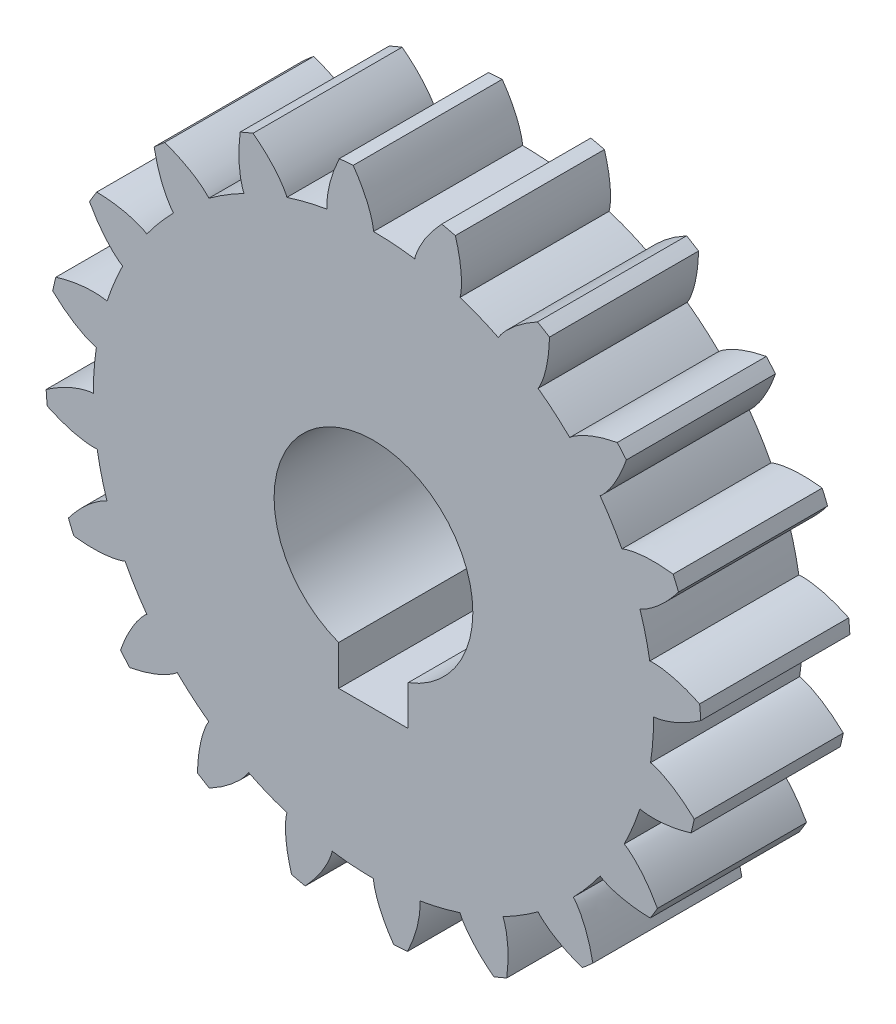
SolidWorks part; units mm, degrees
ref_plane "Front Plane" through (0, 0, 0) normal (0, 0, 1) x (1, 0, 0)
ref_plane "Top Plane" through (0, 0, 0) normal (0, 1, 0) x (1, 0, 0)
ref_plane "Right Plane" through (0, 0, 0) normal (1, 0, 0) x (0, 0, -1)
sketch "Sketch2" plane through (0, 0, 0) normal (0, 0, 1) x (1, 0, 0)
  line L1 (-3.5, -13.3675) -> (3.5, -13.3675)
  line L2 (-3.5, -13.3675) -> (-3.5, -9.3675)
  line L4 (3.5, -13.3675) -> (3.5, -9.3675)
  arc A2 (-4.1537, -27.8823) -> (0, -28.19) centre (0, 0) ccw
  arc A3 (-30.6942, -12.1188) -> (-30.1513, -13.4126) centre (0, 0) ccw
  arc A4 (-32.9368, -2.0406) -> (-32.8203, -3.4389) centre (0, 0) ccw
  arc A5 (-31.9554, 8.2373) -> (-32.2767, 6.8715) centre (0, 0) ccw
  arc A6 (-27.8459, 17.7089) -> (-28.5735, 16.5092) centre (0, 0) ccw
  arc A7 (-21.0107, 25.447) -> (-22.0734, 24.5309) centre (0, 0) ccw
  arc A8 (-12.1188, 30.6942) -> (-13.4126, 30.1513) centre (0, 0) ccw
  arc A9 (-2.0406, 32.9368) -> (-3.4389, 32.8203) centre (0, 0) ccw
  arc A10 (8.2373, 31.9554) -> (6.8715, 32.2767) centre (0, 0) ccw
  arc A11 (17.7089, 27.8459) -> (16.5092, 28.5735) centre (0, 0) ccw
  arc A12 (25.447, 21.0107) -> (24.5309, 22.0734) centre (0, 0) ccw
  arc A13 (30.6942, 12.1188) -> (30.1513, 13.4126) centre (0, 0) ccw
  arc A14 (-25.447, -21.0107) -> (-24.5309, -22.0734) centre (0, 0) ccw
  arc A15 (-17.7089, -27.8459) -> (-16.5092, -28.5735) centre (0, 0) ccw
  arc A16 (-8.2373, -31.9554) -> (-6.8715, -32.2767) centre (0, 0) ccw
  arc A17 (2.0406, -32.9368) -> (3.4389, -32.8203) centre (0, 0) ccw
  arc A18 (12.1188, -30.6942) -> (13.4126, -30.1513) centre (0, 0) ccw
  arc A19 (21.0107, -25.447) -> (22.0734, -24.5309) centre (0, 0) ccw
  arc A20 (27.8459, -17.7089) -> (28.5735, -16.5092) centre (0, 0) ccw
  arc A21 (31.9554, -8.2373) -> (32.2767, -6.8715) centre (0, 0) ccw
  arc A22 (32.9368, 2.0406) -> (32.8203, 3.4389) centre (0, 0) ccw
  arc A23 (4.6657, -27.8012) -> (8.7112, -26.8103) centre (0, 0) ccw
  arc A24 (13.0284, -24.9987) -> (16.5697, -22.8062) centre (0, 0) ccw
  arc A25 (20.1158, -19.7492) -> (22.8062, -16.5697) centre (0, 0) ccw
  arc A26 (25.2341, -12.5665) -> (26.8103, -8.7112) centre (0, 0) ccw
  arc A27 (27.8823, -4.1537) -> (28.19, 0) centre (0, 0) ccw
  arc A28 (27.8012, 4.6657) -> (26.8103, 8.7112) centre (0, 0) ccw
  arc A29 (24.9987, 13.0284) -> (22.8062, 16.5697) centre (0, 0) ccw
  arc A30 (19.7492, 20.1158) -> (16.5697, 22.8062) centre (0, 0) ccw
  arc A31 (12.5665, 25.2341) -> (8.7112, 26.8103) centre (0, 0) ccw
  arc A32 (4.1537, 27.8823) -> (0, 28.19) centre (0, 0) ccw
  arc A33 (-4.6657, 27.8012) -> (-8.7112, 26.8103) centre (0, 0) ccw
  arc A34 (-13.0284, 24.9987) -> (-16.5697, 22.8062) centre (0, 0) ccw
  arc A35 (-20.1158, 19.7492) -> (-22.8062, 16.5697) centre (0, 0) ccw
  arc A36 (-25.2341, 12.5665) -> (-26.8103, 8.7112) centre (0, 0) ccw
  arc A37 (-27.8823, 4.1537) -> (-28.19, 0) centre (0, 0) ccw
  arc A38 (-27.8012, -4.6657) -> (-26.8103, -8.7112) centre (0, 0) ccw
  arc A39 (-24.9987, -13.0284) -> (-22.8062, -16.5697) centre (0, 0) ccw
  arc A40 (-19.7492, -20.1158) -> (-16.5697, -22.8062) centre (0, 0) ccw
  arc A41 (-12.5665, -25.2341) -> (-8.7112, -26.8103) centre (0, 0) ccw
  arc A42 (3.5, -9.3675) -> (-3.5, -9.3675) centre (0, 0) ccw
  spline S0 degree 4 poles (28.19, 0) (28.213, 0.0005) (28.2774, 0.0035) (28.3988, 0.0154) (28.596, 0.0437) (28.9599, 0.1151) (29.504, 0.2622) (30.091, 0.4721) (30.6986, 0.7363) (31.2227, 0.996) (31.6344, 1.2182) (32.1251, 1.5038) (32.7029, 1.8713) (33.3591, 2.3322) (34.0832, 2.8977) (34.7923, 3.5087) (35.4729, 4.1508) (36.1257, 4.8218) (36.7504, 5.5179) (37.2738, 6.1488) (37.7044, 6.7012) (38.0537, 7.1729) (38.3236, 7.5499) (38.5928, 7.942) (38.8447, 8.3199) (39.1085, 8.7342) (39.3339, 9.0971) (39.6556, 9.6405) (39.842, 9.9691) (40.1352, 10.5002) (40.2576, 10.7404) (40.3721, 10.9571) (40.4036, 11.0214) (40.4277, 11.0683) (40.4408, 11.0936) knots 0 0 0 0 0 0.005377 0.015084 0.028532 0.04661 0.092111 0.146842 0.174209 0.201575 0.228941 0.256307 0.307035 0.361767 0.4165 0.471232 0.525964 0.580697 0.635429 0.690161 0.717528 0.744894 0.77226 0.799626 0.826992 0.854358 0.881725 0.909091 0.954545 0.977273 0.988636 0.994318 1 1 1 1 1 construction
  spline S1 degree 4 poles (28.19, 0) (28.213, 0.0005) (28.2774, 0.0035) (28.3988, 0.0154) (28.596, 0.0437) (28.9599, 0.1151) (29.504, 0.2622) (30.091, 0.4721) (30.6986, 0.7363) (31.2227, 0.996) (31.6344, 1.2182) (32.119, 1.5003) (32.4936, 1.7382) (32.7647, 1.9207) (32.9368, 2.0406) knots 0 0 0 0 0 0.005377 0.015084 0.028532 0.04661 0.092111 0.146842 0.174209 0.201575 0.228941 0.256307 0.305396 0.305396 0.305396 0.305396 0.305396
  spline S2 degree 4 poles (24.9987, 13.0284) (25.0194, 13.0385) (25.0779, 13.0656) (25.191, 13.1112) (25.379, 13.1772) (25.7347, 13.2821) (26.2852, 13.4032) (26.9027, 13.4883) (27.5637, 13.5348) (28.1484, 13.5467) (28.6162, 13.54) (29.1763, 13.5138) (29.6185, 13.4759) (29.9433, 13.4394) (30.1513, 13.4126) knots 0 0 0 0 0 0.005377 0.015084 0.028532 0.04661 0.092111 0.146842 0.174209 0.201575 0.228941 0.256307 0.305396 0.305396 0.305396 0.305396 0.305396
  spline S3 degree 4 poles (26.8103, -8.7112) (26.8323, -8.7178) (26.8945, -8.7348) (27.0136, -8.761) (27.2099, -8.7951) (27.5781, -8.8396) (28.141, -8.8679) (28.7641, -8.8496) (29.4237, -8.7862) (30.0023, -8.7011) (30.4626, -8.617) (31.0174, -8.497) (31.6805, -8.326) (32.4471, -8.0905) (33.3105, -7.7764) (34.1737, -7.4144) (35.0194, -7.014) (35.8476, -6.5777) (36.6569, -6.1087) (37.3495, -5.6704) (37.9298, -5.2781) (38.4078, -4.9375) (38.7809, -4.6623) (39.1581, -4.3725) (39.5145, -4.091) (39.8934, -3.7785) (40.2199, -3.503) (40.6938, -3.0856) (40.9726, -2.8306) (41.4156, -2.4162) (41.6062, -2.2255) (41.7821, -2.0548) (41.8319, -2.0034) (41.8693, -1.9662) (41.8896, -1.9462) knots 0 0 0 0 0 0.005377 0.015084 0.028532 0.04661 0.092111 0.146842 0.174209 0.201575 0.228941 0.256307 0.307035 0.361767 0.4165 0.471232 0.525964 0.580697 0.635429 0.690161 0.717528 0.744894 0.77226 0.799626 0.826992 0.854358 0.881725 0.909091 0.954545 0.977273 0.988636 0.994318 1 1 1 1 1 construction
  spline S4 degree 4 poles (26.8103, -8.7112) (26.8323, -8.7178) (26.8945, -8.7348) (27.0136, -8.761) (27.2099, -8.7951) (27.5781, -8.8396) (28.141, -8.8679) (28.7641, -8.8496) (29.4237, -8.7862) (30.0023, -8.7011) (30.4626, -8.617) (31.0106, -8.4984) (31.4404, -8.3879) (31.7546, -8.2982) (31.9554, -8.2373) knots 0 0 0 0 0 0.005377 0.015084 0.028532 0.04661 0.092111 0.146842 0.174209 0.201575 0.228941 0.256307 0.305396 0.305396 0.305396 0.305396 0.305396
  spline S5 degree 4 poles (27.8012, 4.6657) (27.824, 4.669) (27.888, 4.6767) (28.0097, 4.685) (28.2089, 4.6897) (28.5796, 4.6796) (29.1405, 4.6246) (29.7541, 4.5147) (30.3971, 4.3548) (30.9569, 4.1854) (31.3997, 4.0344) (31.9243, 3.8364) (32.3332, 3.6637) (32.6307, 3.5287) (32.8203, 3.4389) knots 0 0 0 0 0 0.005377 0.015084 0.028532 0.04661 0.092111 0.146842 0.174209 0.201575 0.228941 0.256307 0.305396 0.305396 0.305396 0.305396 0.305396
  spline S6 degree 4 poles (22.8062, -16.5697) (22.8251, -16.5828) (22.8789, -16.6182) (22.9842, -16.6799) (23.1604, -16.7729) (23.4967, -16.9291) (24.0234, -17.1299) (24.6216, -17.3051) (25.2685, -17.4485) (25.8451, -17.5464) (26.3088, -17.6087) (26.8736, -17.666) (27.5571, -17.7083) (28.3589, -17.7212) (29.2771, -17.6894) (30.2099, -17.6118) (31.138, -17.4924) (32.0605, -17.3333) (32.9751, -17.1373) (33.7693, -16.9345) (34.4423, -16.7407) (35.0022, -16.5645) (35.4421, -16.418) (35.8904, -16.259) (36.3163, -16.1014) (36.7732, -15.9213) (37.1689, -15.7602) (37.7486, -15.5096) (38.0925, -15.3533) (38.6419, -15.096) (38.8821, -14.9736) (39.1021, -14.8656) (39.1654, -14.8321) (39.2124, -14.8083) (39.2379, -14.7955) knots 0 0 0 0 0 0.005377 0.015084 0.028532 0.04661 0.092111 0.146842 0.174209 0.201575 0.228941 0.256307 0.307035 0.361767 0.4165 0.471232 0.525964 0.580697 0.635429 0.690161 0.717528 0.744894 0.77226 0.799626 0.826992 0.854358 0.881725 0.909091 0.954545 0.977273 0.988636 0.994318 1 1 1 1 1 construction
  spline S7 degree 4 poles (22.8062, -16.5697) (22.8251, -16.5828) (22.8789, -16.6182) (22.9842, -16.6799) (23.1604, -16.7729) (23.4967, -16.9291) (24.0234, -17.1299) (24.6216, -17.3051) (25.2685, -17.4485) (25.8451, -17.5464) (26.3088, -17.6087) (26.8667, -17.6653) (27.3096, -17.693) (27.6362, -17.7048) (27.8459, -17.7089) knots 0 0 0 0 0 0.005377 0.015084 0.028532 0.04661 0.092111 0.146842 0.174209 0.201575 0.228941 0.256307 0.305396 0.305396 0.305396 0.305396 0.305396
  spline S8 degree 4 poles (27.8823, -4.1537) (27.905, -4.1576) (27.9682, -4.1701) (28.0865, -4.1998) (28.2774, -4.2568) (28.6269, -4.381) (29.1434, -4.6066) (29.6929, -4.9008) (30.2551, -5.2516) (30.7351, -5.5857) (31.1096, -5.8661) (31.5473, -6.2166) (31.8828, -6.5071) (32.1241, -6.7275) (32.2767, -6.8715) knots 0 0 0 0 0 0.005377 0.015084 0.028532 0.04661 0.092111 0.146842 0.174209 0.201575 0.228941 0.256307 0.305396 0.305396 0.305396 0.305396 0.305396
  spline S9 degree 4 poles (16.5697, -22.8062) (16.5836, -22.8245) (16.6239, -22.8748) (16.7049, -22.966) (16.8437, -23.1089) (17.1153, -23.3614) (17.5541, -23.7152) (18.069, -24.0666) (18.6399, -24.4029) (19.158, -24.6742) (19.5798, -24.8768) (20.0993, -25.1058) (20.7362, -25.3572) (21.4948, -25.6172) (22.3779, -25.8707) (23.289, -26.0852) (24.2086, -26.2584) (25.1351, -26.3921) (26.0654, -26.4884) (26.8834, -26.541) (27.5834, -26.5646) (28.1704, -26.57) (28.634, -26.5667) (29.1095, -26.554) (29.5633, -26.5357) (30.0535, -26.5056) (30.4796, -26.4747) (31.1083, -26.4155) (31.4837, -26.3731) (32.0857, -26.2982) (32.352, -26.256) (32.5946, -26.2213) (32.6651, -26.2089) (32.7172, -26.2009) (32.7454, -26.1966) knots 0 0 0 0 0 0.005377 0.015084 0.028532 0.04661 0.092111 0.146842 0.174209 0.201575 0.228941 0.256307 0.307035 0.361767 0.4165 0.471232 0.525964 0.580697 0.635429 0.690161 0.717528 0.744894 0.77226 0.799626 0.826992 0.854358 0.881725 0.909091 0.954545 0.977273 0.988636 0.994318 1 1 1 1 1 construction
  spline S10 degree 4 poles (16.5697, -22.8062) (16.5836, -22.8245) (16.6239, -22.8748) (16.7049, -22.966) (16.8437, -23.1089) (17.1153, -23.3614) (17.5541, -23.7152) (18.069, -24.0666) (18.6399, -24.4029) (19.158, -24.6742) (19.5798, -24.8768) (20.0928, -25.103) (20.5055, -25.2662) (20.8125, -25.3783) (21.0107, -25.447) knots 0 0 0 0 0 0.005377 0.015084 0.028532 0.04661 0.092111 0.146842 0.174209 0.201575 0.228941 0.256307 0.305396 0.305396 0.305396 0.305396 0.305396
  spline S11 degree 4 poles (25.2341, -12.5665) (25.2544, -12.5772) (25.3107, -12.6086) (25.4141, -12.6734) (25.578, -12.7867) (25.872, -13.0128) (26.2935, -13.387) (26.7252, -13.8365) (27.1514, -14.3439) (27.5047, -14.81) (27.7743, -15.1924) (28.0823, -15.661) (28.3116, -16.041) (28.4729, -16.3251) (28.5735, -16.5092) knots 0 0 0 0 0 0.005377 0.015084 0.028532 0.04661 0.092111 0.146842 0.174209 0.201575 0.228941 0.256307 0.305396 0.305396 0.305396 0.305396 0.305396
  spline S12 degree 4 poles (8.7112, -26.8103) (8.7188, -26.832) (8.7415, -26.8923) (8.7904, -27.0041) (8.8783, -27.1829) (9.0586, -27.5069) (9.3666, -27.979) (9.7476, -28.4723) (10.1866, -28.9686) (10.5956, -29.3867) (10.9341, -29.7097) (11.3574, -30.088) (11.8854, -30.524) (12.5266, -31.0057) (13.2882, -31.5197) (14.0884, -32.0052) (14.9094, -32.4541) (15.7493, -32.8676) (16.6043, -33.2466) (17.366, -33.5494) (18.0245, -33.7882) (18.581, -33.9747) (19.023, -34.1148) (19.4791, -34.2497) (19.9164, -34.3725) (20.3919, -34.4953) (20.8067, -34.5976) (21.4229, -34.7356) (21.793, -34.8113) (22.3887, -34.9261) (22.655, -34.9683) (22.8965, -35.0102) (22.9674, -35.0203) (23.0194, -35.0287) (23.0476, -35.0333) knots 0 0 0 0 0 0.005377 0.015084 0.028532 0.04661 0.092111 0.146842 0.174209 0.201575 0.228941 0.256307 0.307035 0.361767 0.4165 0.471232 0.525964 0.580697 0.635429 0.690161 0.717528 0.744894 0.77226 0.799626 0.826992 0.854358 0.881725 0.909091 0.954545 0.977273 0.988636 0.994318 1 1 1 1 1 construction
  spline S13 degree 4 poles (8.7112, -26.8103) (8.7188, -26.832) (8.7415, -26.8923) (8.7904, -27.0041) (8.8783, -27.1829) (9.0586, -27.5069) (9.3666, -27.979) (9.7476, -28.4723) (10.1866, -28.9686) (10.5956, -29.3867) (10.9341, -29.7097) (11.3522, -30.0834) (11.6942, -30.3661) (11.9515, -30.5676) (12.1188, -30.6942) knots 0 0 0 0 0 0.005377 0.015084 0.028532 0.04661 0.092111 0.146842 0.174209 0.201575 0.228941 0.256307 0.305396 0.305396 0.305396 0.305396 0.305396
  spline S14 degree 4 poles (20.1158, -19.7492) (20.1318, -19.7657) (20.1756, -19.813) (20.2539, -19.9065) (20.3748, -20.0649) (20.5845, -20.3708) (20.8698, -20.8569) (21.1415, -21.4179) (21.39, -22.0321) (21.582, -22.5846) (21.7202, -23.0316) (21.8683, -23.5724) (21.969, -24.0046) (22.0346, -24.3247) (22.0734, -24.5309) knots 0 0 0 0 0 0.005377 0.015084 0.028532 0.04661 0.092111 0.146842 0.174209 0.201575 0.228941 0.256307 0.305396 0.305396 0.305396 0.305396 0.305396
  spline S15 degree 4 poles (0, -28.19) (0.0005, -28.213) (0.0035, -28.2774) (0.0154, -28.3988) (0.0437, -28.596) (0.1151, -28.9599) (0.2622, -29.504) (0.4721, -30.091) (0.7363, -30.6986) (0.996, -31.2227) (1.2182, -31.6344) (1.5038, -32.1251) (1.8713, -32.7029) (2.3322, -33.3591) (2.8977, -34.0832) (3.5087, -34.7923) (4.1508, -35.4729) (4.8218, -36.1257) (5.5179, -36.7504) (6.1488, -37.2738) (6.7012, -37.7044) (7.1729, -38.0537) (7.5499, -38.3236) (7.942, -38.5928) (8.3199, -38.8447) (8.7342, -39.1085) (9.0971, -39.3339) (9.6405, -39.6556) (9.9691, -39.842) (10.5002, -40.1352) (10.7404, -40.2576) (10.9571, -40.3721) (11.0214, -40.4036) (11.0683, -40.4277) (11.0936, -40.4408) knots 0 0 0 0 0 0.005377 0.015084 0.028532 0.04661 0.092111 0.146842 0.174209 0.201575 0.228941 0.256307 0.307035 0.361767 0.4165 0.471232 0.525964 0.580697 0.635429 0.690161 0.717528 0.744894 0.77226 0.799626 0.826992 0.854358 0.881725 0.909091 0.954545 0.977273 0.988636 0.994318 1 1 1 1 1 construction
  spline S16 degree 4 poles (0, -28.19) (0.0005, -28.213) (0.0035, -28.2774) (0.0154, -28.3988) (0.0437, -28.596) (0.1151, -28.9599) (0.2622, -29.504) (0.4721, -30.091) (0.7363, -30.6986) (0.996, -31.2227) (1.2182, -31.6344) (1.5003, -32.119) (1.7382, -32.4936) (1.9207, -32.7647) (2.0406, -32.9368) knots 0 0 0 0 0 0.005377 0.015084 0.028532 0.04661 0.092111 0.146842 0.174209 0.201575 0.228941 0.256307 0.305396 0.305396 0.305396 0.305396 0.305396
  spline S17 degree 4 poles (13.0284, -24.9987) (13.0385, -25.0194) (13.0656, -25.0779) (13.1112, -25.191) (13.1772, -25.379) (13.2821, -25.7347) (13.4032, -26.2852) (13.4883, -26.9027) (13.5348, -27.5637) (13.5467, -28.1484) (13.54, -28.6162) (13.5138, -29.1763) (13.4759, -29.6185) (13.4394, -29.9433) (13.4126, -30.1513) knots 0 0 0 0 0 0.005377 0.015084 0.028532 0.04661 0.092111 0.146842 0.174209 0.201575 0.228941 0.256307 0.305396 0.305396 0.305396 0.305396 0.305396
  spline S18 degree 4 poles (-8.7112, -26.8103) (-8.7178, -26.8323) (-8.7348, -26.8945) (-8.761, -27.0136) (-8.7951, -27.2099) (-8.8396, -27.5781) (-8.8679, -28.141) (-8.8496, -28.7641) (-8.7862, -29.4237) (-8.7011, -30.0023) (-8.617, -30.4626) (-8.497, -31.0174) (-8.326, -31.6805) (-8.0905, -32.4471) (-7.7764, -33.3105) (-7.4144, -34.1737) (-7.014, -35.0194) (-6.5777, -35.8476) (-6.1087, -36.6569) (-5.6704, -37.3495) (-5.2781, -37.9298) (-4.9375, -38.4078) (-4.6623, -38.7809) (-4.3725, -39.1581) (-4.091, -39.5145) (-3.7785, -39.8934) (-3.503, -40.2199) (-3.0856, -40.6938) (-2.8306, -40.9726) (-2.4162, -41.4156) (-2.2255, -41.6062) (-2.0548, -41.7821) (-2.0034, -41.8319) (-1.9662, -41.8693) (-1.9462, -41.8896) knots 0 0 0 0 0 0.005377 0.015084 0.028532 0.04661 0.092111 0.146842 0.174209 0.201575 0.228941 0.256307 0.307035 0.361767 0.4165 0.471232 0.525964 0.580697 0.635429 0.690161 0.717528 0.744894 0.77226 0.799626 0.826992 0.854358 0.881725 0.909091 0.954545 0.977273 0.988636 0.994318 1 1 1 1 1 construction
  spline S19 degree 4 poles (-8.7112, -26.8103) (-8.7178, -26.8323) (-8.7348, -26.8945) (-8.761, -27.0136) (-8.7951, -27.2099) (-8.8396, -27.5781) (-8.8679, -28.141) (-8.8496, -28.7641) (-8.7862, -29.4237) (-8.7011, -30.0023) (-8.617, -30.4626) (-8.4984, -31.0106) (-8.3879, -31.4404) (-8.2982, -31.7546) (-8.2373, -31.9554) knots 0 0 0 0 0 0.005377 0.015084 0.028532 0.04661 0.092111 0.146842 0.174209 0.201575 0.228941 0.256307 0.305396 0.305396 0.305396 0.305396 0.305396
  spline S20 degree 4 poles (4.6657, -27.8012) (4.669, -27.824) (4.6767, -27.888) (4.685, -28.0097) (4.6897, -28.2089) (4.6796, -28.5796) (4.6246, -29.1405) (4.5147, -29.7541) (4.3548, -30.3971) (4.1854, -30.9569) (4.0344, -31.3997) (3.8364, -31.9243) (3.6637, -32.3332) (3.5287, -32.6307) (3.4389, -32.8203) knots 0 0 0 0 0 0.005377 0.015084 0.028532 0.04661 0.092111 0.146842 0.174209 0.201575 0.228941 0.256307 0.305396 0.305396 0.305396 0.305396 0.305396
  spline S21 degree 4 poles (-16.5697, -22.8062) (-16.5828, -22.8251) (-16.6182, -22.8789) (-16.6799, -22.9842) (-16.7729, -23.1604) (-16.9291, -23.4967) (-17.1299, -24.0234) (-17.3051, -24.6216) (-17.4485, -25.2685) (-17.5464, -25.8451) (-17.6087, -26.3088) (-17.666, -26.8736) (-17.7083, -27.5571) (-17.7212, -28.3589) (-17.6894, -29.2771) (-17.6118, -30.2099) (-17.4924, -31.138) (-17.3333, -32.0605) (-17.1373, -32.9751) (-16.9345, -33.7693) (-16.7407, -34.4423) (-16.5645, -35.0022) (-16.418, -35.4421) (-16.259, -35.8904) (-16.1014, -36.3163) (-15.9213, -36.7732) (-15.7602, -37.1689) (-15.5096, -37.7486) (-15.3533, -38.0925) (-15.096, -38.6419) (-14.9736, -38.8821) (-14.8656, -39.1021) (-14.8321, -39.1654) (-14.8083, -39.2124) (-14.7955, -39.2379) knots 0 0 0 0 0 0.005377 0.015084 0.028532 0.04661 0.092111 0.146842 0.174209 0.201575 0.228941 0.256307 0.307035 0.361767 0.4165 0.471232 0.525964 0.580697 0.635429 0.690161 0.717528 0.744894 0.77226 0.799626 0.826992 0.854358 0.881725 0.909091 0.954545 0.977273 0.988636 0.994318 1 1 1 1 1 construction
  spline S22 degree 4 poles (-16.5697, -22.8062) (-16.5828, -22.8251) (-16.6182, -22.8789) (-16.6799, -22.9842) (-16.7729, -23.1604) (-16.9291, -23.4967) (-17.1299, -24.0234) (-17.3051, -24.6216) (-17.4485, -25.2685) (-17.5464, -25.8451) (-17.6087, -26.3088) (-17.6653, -26.8667) (-17.693, -27.3096) (-17.7048, -27.6362) (-17.7089, -27.8459) knots 0 0 0 0 0 0.005377 0.015084 0.028532 0.04661 0.092111 0.146842 0.174209 0.201575 0.228941 0.256307 0.305396 0.305396 0.305396 0.305396 0.305396
  spline S23 degree 4 poles (-4.1537, -27.8823) (-4.1576, -27.905) (-4.1701, -27.9682) (-4.1998, -28.0865) (-4.2568, -28.2774) (-4.381, -28.6269) (-4.6066, -29.1434) (-4.9008, -29.6929) (-5.2516, -30.2551) (-5.5857, -30.7351) (-5.8661, -31.1096) (-6.2166, -31.5473) (-6.5071, -31.8828) (-6.7275, -32.1241) (-6.8715, -32.2767) knots 0 0 0 0 0 0.005377 0.015084 0.028532 0.04661 0.092111 0.146842 0.174209 0.201575 0.228941 0.256307 0.305396 0.305396 0.305396 0.305396 0.305396
  spline S24 degree 4 poles (-22.8062, -16.5697) (-22.8245, -16.5836) (-22.8748, -16.6239) (-22.966, -16.7049) (-23.1089, -16.8437) (-23.3614, -17.1153) (-23.7152, -17.5541) (-24.0666, -18.069) (-24.4029, -18.6399) (-24.6742, -19.158) (-24.8768, -19.5798) (-25.1058, -20.0993) (-25.3572, -20.7362) (-25.6172, -21.4948) (-25.8707, -22.3779) (-26.0852, -23.289) (-26.2584, -24.2086) (-26.3921, -25.1351) (-26.4884, -26.0654) (-26.541, -26.8834) (-26.5646, -27.5834) (-26.57, -28.1704) (-26.5667, -28.634) (-26.554, -29.1095) (-26.5357, -29.5633) (-26.5056, -30.0535) (-26.4747, -30.4796) (-26.4155, -31.1083) (-26.3731, -31.4837) (-26.2982, -32.0857) (-26.256, -32.352) (-26.2213, -32.5946) (-26.2089, -32.6651) (-26.2009, -32.7172) (-26.1966, -32.7454) knots 0 0 0 0 0 0.005377 0.015084 0.028532 0.04661 0.092111 0.146842 0.174209 0.201575 0.228941 0.256307 0.307035 0.361767 0.4165 0.471232 0.525964 0.580697 0.635429 0.690161 0.717528 0.744894 0.77226 0.799626 0.826992 0.854358 0.881725 0.909091 0.954545 0.977273 0.988636 0.994318 1 1 1 1 1 construction
  spline S25 degree 4 poles (-22.8062, -16.5697) (-22.8245, -16.5836) (-22.8748, -16.6239) (-22.966, -16.7049) (-23.1089, -16.8437) (-23.3614, -17.1153) (-23.7152, -17.5541) (-24.0666, -18.069) (-24.4029, -18.6399) (-24.6742, -19.158) (-24.8768, -19.5798) (-25.103, -20.0928) (-25.2662, -20.5055) (-25.3783, -20.8125) (-25.447, -21.0107) knots 0 0 0 0 0 0.005377 0.015084 0.028532 0.04661 0.092111 0.146842 0.174209 0.201575 0.228941 0.256307 0.305396 0.305396 0.305396 0.305396 0.305396
  spline S26 degree 4 poles (-12.5665, -25.2341) (-12.5772, -25.2544) (-12.6086, -25.3107) (-12.6734, -25.4141) (-12.7867, -25.578) (-13.0128, -25.872) (-13.387, -26.2935) (-13.8365, -26.7252) (-14.3439, -27.1514) (-14.81, -27.5047) (-15.1924, -27.7743) (-15.661, -28.0823) (-16.041, -28.3116) (-16.3251, -28.4729) (-16.5092, -28.5735) knots 0 0 0 0 0 0.005377 0.015084 0.028532 0.04661 0.092111 0.146842 0.174209 0.201575 0.228941 0.256307 0.305396 0.305396 0.305396 0.305396 0.305396
  spline S27 degree 4 poles (-26.8103, -8.7112) (-26.832, -8.7188) (-26.8923, -8.7415) (-27.0041, -8.7904) (-27.1829, -8.8783) (-27.5069, -9.0586) (-27.979, -9.3666) (-28.4723, -9.7476) (-28.9686, -10.1866) (-29.3867, -10.5956) (-29.7097, -10.9341) (-30.088, -11.3574) (-30.524, -11.8854) (-31.0057, -12.5266) (-31.5197, -13.2882) (-32.0052, -14.0884) (-32.4541, -14.9094) (-32.8676, -15.7493) (-33.2466, -16.6043) (-33.5494, -17.366) (-33.7882, -18.0245) (-33.9747, -18.581) (-34.1148, -19.023) (-34.2497, -19.4791) (-34.3725, -19.9164) (-34.4953, -20.3919) (-34.5976, -20.8067) (-34.7356, -21.4229) (-34.8113, -21.793) (-34.9261, -22.3887) (-34.9683, -22.655) (-35.0102, -22.8965) (-35.0203, -22.9674) (-35.0287, -23.0194) (-35.0333, -23.0476) knots 0 0 0 0 0 0.005377 0.015084 0.028532 0.04661 0.092111 0.146842 0.174209 0.201575 0.228941 0.256307 0.307035 0.361767 0.4165 0.471232 0.525964 0.580697 0.635429 0.690161 0.717528 0.744894 0.77226 0.799626 0.826992 0.854358 0.881725 0.909091 0.954545 0.977273 0.988636 0.994318 1 1 1 1 1 construction
  spline S28 degree 4 poles (-26.8103, -8.7112) (-26.832, -8.7188) (-26.8923, -8.7415) (-27.0041, -8.7904) (-27.1829, -8.8783) (-27.5069, -9.0586) (-27.979, -9.3666) (-28.4723, -9.7476) (-28.9686, -10.1866) (-29.3867, -10.5956) (-29.7097, -10.9341) (-30.0834, -11.3522) (-30.3661, -11.6942) (-30.5676, -11.9515) (-30.6942, -12.1188) knots 0 0 0 0 0 0.005377 0.015084 0.028532 0.04661 0.092111 0.146842 0.174209 0.201575 0.228941 0.256307 0.305396 0.305396 0.305396 0.305396 0.305396
  spline S29 degree 4 poles (-19.7492, -20.1158) (-19.7657, -20.1318) (-19.813, -20.1756) (-19.9065, -20.2539) (-20.0649, -20.3748) (-20.3708, -20.5845) (-20.8569, -20.8698) (-21.4179, -21.1415) (-22.0321, -21.39) (-22.5846, -21.582) (-23.0316, -21.7202) (-23.5724, -21.8683) (-24.0046, -21.969) (-24.3247, -22.0346) (-24.5309, -22.0734) knots 0 0 0 0 0 0.005377 0.015084 0.028532 0.04661 0.092111 0.146842 0.174209 0.201575 0.228941 0.256307 0.305396 0.305396 0.305396 0.305396 0.305396
  spline S30 degree 4 poles (-28.19, 0) (-28.213, -0.0005) (-28.2774, -0.0035) (-28.3988, -0.0154) (-28.596, -0.0437) (-28.9599, -0.1151) (-29.504, -0.2622) (-30.091, -0.4721) (-30.6986, -0.7363) (-31.2227, -0.996) (-31.6344, -1.2182) (-32.1251, -1.5038) (-32.7029, -1.8713) (-33.3591, -2.3322) (-34.0832, -2.8977) (-34.7923, -3.5087) (-35.4729, -4.1508) (-36.1257, -4.8218) (-36.7504, -5.5179) (-37.2738, -6.1488) (-37.7044, -6.7012) (-38.0537, -7.1729) (-38.3236, -7.5499) (-38.5928, -7.942) (-38.8447, -8.3199) (-39.1085, -8.7342) (-39.3339, -9.0971) (-39.6556, -9.6405) (-39.842, -9.9691) (-40.1352, -10.5002) (-40.2576, -10.7404) (-40.3721, -10.9571) (-40.4036, -11.0214) (-40.4277, -11.0683) (-40.4408, -11.0936) knots 0 0 0 0 0 0.005377 0.015084 0.028532 0.04661 0.092111 0.146842 0.174209 0.201575 0.228941 0.256307 0.307035 0.361767 0.4165 0.471232 0.525964 0.580697 0.635429 0.690161 0.717528 0.744894 0.77226 0.799626 0.826992 0.854358 0.881725 0.909091 0.954545 0.977273 0.988636 0.994318 1 1 1 1 1 construction
  spline S31 degree 4 poles (-28.19, 0) (-28.213, -0.0005) (-28.2774, -0.0035) (-28.3988, -0.0154) (-28.596, -0.0437) (-28.9599, -0.1151) (-29.504, -0.2622) (-30.091, -0.4721) (-30.6986, -0.7363) (-31.2227, -0.996) (-31.6344, -1.2182) (-32.119, -1.5003) (-32.4936, -1.7382) (-32.7647, -1.9207) (-32.9368, -2.0406) knots 0 0 0 0 0 0.005377 0.015084 0.028532 0.04661 0.092111 0.146842 0.174209 0.201575 0.228941 0.256307 0.305396 0.305396 0.305396 0.305396 0.305396
  spline S32 degree 4 poles (-24.9987, -13.0284) (-25.0194, -13.0385) (-25.0779, -13.0656) (-25.191, -13.1112) (-25.379, -13.1772) (-25.7347, -13.2821) (-26.2852, -13.4032) (-26.9027, -13.4883) (-27.5637, -13.5348) (-28.1484, -13.5467) (-28.6162, -13.54) (-29.1763, -13.5138) (-29.6185, -13.4759) (-29.9433, -13.4394) (-30.1513, -13.4126) knots 0 0 0 0 0 0.005377 0.015084 0.028532 0.04661 0.092111 0.146842 0.174209 0.201575 0.228941 0.256307 0.305396 0.305396 0.305396 0.305396 0.305396
  spline S33 degree 4 poles (-26.8103, 8.7112) (-26.8323, 8.7178) (-26.8945, 8.7348) (-27.0136, 8.761) (-27.2099, 8.7951) (-27.5781, 8.8396) (-28.141, 8.8679) (-28.7641, 8.8496) (-29.4237, 8.7862) (-30.0023, 8.7011) (-30.4626, 8.617) (-31.0174, 8.497) (-31.6805, 8.326) (-32.4471, 8.0905) (-33.3105, 7.7764) (-34.1737, 7.4144) (-35.0194, 7.014) (-35.8476, 6.5777) (-36.6569, 6.1087) (-37.3495, 5.6704) (-37.9298, 5.2781) (-38.4078, 4.9375) (-38.7809, 4.6623) (-39.1581, 4.3725) (-39.5145, 4.091) (-39.8934, 3.7785) (-40.2199, 3.503) (-40.6938, 3.0856) (-40.9726, 2.8306) (-41.4156, 2.4162) (-41.6062, 2.2255) (-41.7821, 2.0548) (-41.8319, 2.0034) (-41.8693, 1.9662) (-41.8896, 1.9462) knots 0 0 0 0 0 0.005377 0.015084 0.028532 0.04661 0.092111 0.146842 0.174209 0.201575 0.228941 0.256307 0.307035 0.361767 0.4165 0.471232 0.525964 0.580697 0.635429 0.690161 0.717528 0.744894 0.77226 0.799626 0.826992 0.854358 0.881725 0.909091 0.954545 0.977273 0.988636 0.994318 1 1 1 1 1 construction
  spline S34 degree 4 poles (-26.8103, 8.7112) (-26.8323, 8.7178) (-26.8945, 8.7348) (-27.0136, 8.761) (-27.2099, 8.7951) (-27.5781, 8.8396) (-28.141, 8.8679) (-28.7641, 8.8496) (-29.4237, 8.7862) (-30.0023, 8.7011) (-30.4626, 8.617) (-31.0106, 8.4984) (-31.4404, 8.3879) (-31.7546, 8.2982) (-31.9554, 8.2373) knots 0 0 0 0 0 0.005377 0.015084 0.028532 0.04661 0.092111 0.146842 0.174209 0.201575 0.228941 0.256307 0.305396 0.305396 0.305396 0.305396 0.305396
  spline S35 degree 4 poles (-27.8012, -4.6657) (-27.824, -4.669) (-27.888, -4.6767) (-28.0097, -4.685) (-28.2089, -4.6897) (-28.5796, -4.6796) (-29.1405, -4.6246) (-29.7541, -4.5147) (-30.3971, -4.3548) (-30.9569, -4.1854) (-31.3997, -4.0344) (-31.9243, -3.8364) (-32.3332, -3.6637) (-32.6307, -3.5287) (-32.8203, -3.4389) knots 0 0 0 0 0 0.005377 0.015084 0.028532 0.04661 0.092111 0.146842 0.174209 0.201575 0.228941 0.256307 0.305396 0.305396 0.305396 0.305396 0.305396
  spline S36 degree 4 poles (-22.8062, 16.5697) (-22.8251, 16.5828) (-22.8789, 16.6182) (-22.9842, 16.6799) (-23.1604, 16.7729) (-23.4967, 16.9291) (-24.0234, 17.1299) (-24.6216, 17.3051) (-25.2685, 17.4485) (-25.8451, 17.5464) (-26.3088, 17.6087) (-26.8736, 17.666) (-27.5571, 17.7083) (-28.3589, 17.7212) (-29.2771, 17.6894) (-30.2099, 17.6118) (-31.138, 17.4924) (-32.0605, 17.3333) (-32.9751, 17.1373) (-33.7693, 16.9345) (-34.4423, 16.7407) (-35.0022, 16.5645) (-35.4421, 16.418) (-35.8904, 16.259) (-36.3163, 16.1014) (-36.7732, 15.9213) (-37.1689, 15.7602) (-37.7486, 15.5096) (-38.0925, 15.3533) (-38.6419, 15.096) (-38.8821, 14.9736) (-39.1021, 14.8656) (-39.1654, 14.8321) (-39.2124, 14.8083) (-39.2379, 14.7955) knots 0 0 0 0 0 0.005377 0.015084 0.028532 0.04661 0.092111 0.146842 0.174209 0.201575 0.228941 0.256307 0.307035 0.361767 0.4165 0.471232 0.525964 0.580697 0.635429 0.690161 0.717528 0.744894 0.77226 0.799626 0.826992 0.854358 0.881725 0.909091 0.954545 0.977273 0.988636 0.994318 1 1 1 1 1 construction
  spline S37 degree 4 poles (-22.8062, 16.5697) (-22.8251, 16.5828) (-22.8789, 16.6182) (-22.9842, 16.6799) (-23.1604, 16.7729) (-23.4967, 16.9291) (-24.0234, 17.1299) (-24.6216, 17.3051) (-25.2685, 17.4485) (-25.8451, 17.5464) (-26.3088, 17.6087) (-26.8667, 17.6653) (-27.3096, 17.693) (-27.6362, 17.7048) (-27.8459, 17.7089) knots 0 0 0 0 0 0.005377 0.015084 0.028532 0.04661 0.092111 0.146842 0.174209 0.201575 0.228941 0.256307 0.305396 0.305396 0.305396 0.305396 0.305396
  spline S38 degree 4 poles (-27.8823, 4.1537) (-27.905, 4.1576) (-27.9682, 4.1701) (-28.0865, 4.1998) (-28.2774, 4.2568) (-28.6269, 4.381) (-29.1434, 4.6066) (-29.6929, 4.9008) (-30.2551, 5.2516) (-30.7351, 5.5857) (-31.1096, 5.8661) (-31.5473, 6.2166) (-31.8828, 6.5071) (-32.1241, 6.7275) (-32.2767, 6.8715) knots 0 0 0 0 0 0.005377 0.015084 0.028532 0.04661 0.092111 0.146842 0.174209 0.201575 0.228941 0.256307 0.305396 0.305396 0.305396 0.305396 0.305396
  spline S39 degree 4 poles (-16.5697, 22.8062) (-16.5836, 22.8245) (-16.6239, 22.8748) (-16.7049, 22.966) (-16.8437, 23.1089) (-17.1153, 23.3614) (-17.5541, 23.7152) (-18.069, 24.0666) (-18.6399, 24.4029) (-19.158, 24.6742) (-19.5798, 24.8768) (-20.0993, 25.1058) (-20.7362, 25.3572) (-21.4948, 25.6172) (-22.3779, 25.8707) (-23.289, 26.0852) (-24.2086, 26.2584) (-25.1351, 26.3921) (-26.0654, 26.4884) (-26.8834, 26.541) (-27.5834, 26.5646) (-28.1704, 26.57) (-28.634, 26.5667) (-29.1095, 26.554) (-29.5633, 26.5357) (-30.0535, 26.5056) (-30.4796, 26.4747) (-31.1083, 26.4155) (-31.4837, 26.3731) (-32.0857, 26.2982) (-32.352, 26.256) (-32.5946, 26.2213) (-32.6651, 26.2089) (-32.7172, 26.2009) (-32.7454, 26.1966) knots 0 0 0 0 0 0.005377 0.015084 0.028532 0.04661 0.092111 0.146842 0.174209 0.201575 0.228941 0.256307 0.307035 0.361767 0.4165 0.471232 0.525964 0.580697 0.635429 0.690161 0.717528 0.744894 0.77226 0.799626 0.826992 0.854358 0.881725 0.909091 0.954545 0.977273 0.988636 0.994318 1 1 1 1 1 construction
  spline S40 degree 4 poles (-16.5697, 22.8062) (-16.5836, 22.8245) (-16.6239, 22.8748) (-16.7049, 22.966) (-16.8437, 23.1089) (-17.1153, 23.3614) (-17.5541, 23.7152) (-18.069, 24.0666) (-18.6399, 24.4029) (-19.158, 24.6742) (-19.5798, 24.8768) (-20.0928, 25.103) (-20.5055, 25.2662) (-20.8125, 25.3783) (-21.0107, 25.447) knots 0 0 0 0 0 0.005377 0.015084 0.028532 0.04661 0.092111 0.146842 0.174209 0.201575 0.228941 0.256307 0.305396 0.305396 0.305396 0.305396 0.305396
  spline S41 degree 4 poles (-25.2341, 12.5665) (-25.2544, 12.5772) (-25.3107, 12.6086) (-25.4141, 12.6734) (-25.578, 12.7867) (-25.872, 13.0128) (-26.2935, 13.387) (-26.7252, 13.8365) (-27.1514, 14.3439) (-27.5047, 14.81) (-27.7743, 15.1924) (-28.0823, 15.661) (-28.3116, 16.041) (-28.4729, 16.3251) (-28.5735, 16.5092) knots 0 0 0 0 0 0.005377 0.015084 0.028532 0.04661 0.092111 0.146842 0.174209 0.201575 0.228941 0.256307 0.305396 0.305396 0.305396 0.305396 0.305396
  spline S42 degree 4 poles (-8.7112, 26.8103) (-8.7188, 26.832) (-8.7415, 26.8923) (-8.7904, 27.0041) (-8.8783, 27.1829) (-9.0586, 27.5069) (-9.3666, 27.979) (-9.7476, 28.4723) (-10.1866, 28.9686) (-10.5956, 29.3867) (-10.9341, 29.7097) (-11.3574, 30.088) (-11.8854, 30.524) (-12.5266, 31.0057) (-13.2882, 31.5197) (-14.0884, 32.0052) (-14.9094, 32.4541) (-15.7493, 32.8676) (-16.6043, 33.2466) (-17.366, 33.5494) (-18.0245, 33.7882) (-18.581, 33.9747) (-19.023, 34.1148) (-19.4791, 34.2497) (-19.9164, 34.3725) (-20.3919, 34.4953) (-20.8067, 34.5976) (-21.4229, 34.7356) (-21.793, 34.8113) (-22.3887, 34.9261) (-22.655, 34.9683) (-22.8965, 35.0102) (-22.9674, 35.0203) (-23.0194, 35.0287) (-23.0476, 35.0333) knots 0 0 0 0 0 0.005377 0.015084 0.028532 0.04661 0.092111 0.146842 0.174209 0.201575 0.228941 0.256307 0.307035 0.361767 0.4165 0.471232 0.525964 0.580697 0.635429 0.690161 0.717528 0.744894 0.77226 0.799626 0.826992 0.854358 0.881725 0.909091 0.954545 0.977273 0.988636 0.994318 1 1 1 1 1 construction
  spline S43 degree 4 poles (-8.7112, 26.8103) (-8.7188, 26.832) (-8.7415, 26.8923) (-8.7904, 27.0041) (-8.8783, 27.1829) (-9.0586, 27.5069) (-9.3666, 27.979) (-9.7476, 28.4723) (-10.1866, 28.9686) (-10.5956, 29.3867) (-10.9341, 29.7097) (-11.3522, 30.0834) (-11.6942, 30.3661) (-11.9515, 30.5676) (-12.1188, 30.6942) knots 0 0 0 0 0 0.005377 0.015084 0.028532 0.04661 0.092111 0.146842 0.174209 0.201575 0.228941 0.256307 0.305396 0.305396 0.305396 0.305396 0.305396
  spline S44 degree 4 poles (-20.1158, 19.7492) (-20.1318, 19.7657) (-20.1756, 19.813) (-20.2539, 19.9065) (-20.3748, 20.0649) (-20.5845, 20.3708) (-20.8698, 20.8569) (-21.1415, 21.4179) (-21.39, 22.0321) (-21.582, 22.5846) (-21.7202, 23.0316) (-21.8683, 23.5724) (-21.969, 24.0046) (-22.0346, 24.3247) (-22.0734, 24.5309) knots 0 0 0 0 0 0.005377 0.015084 0.028532 0.04661 0.092111 0.146842 0.174209 0.201575 0.228941 0.256307 0.305396 0.305396 0.305396 0.305396 0.305396
  spline S45 degree 4 poles (0, 28.19) (-0.0005, 28.213) (-0.0035, 28.2774) (-0.0154, 28.3988) (-0.0437, 28.596) (-0.1151, 28.9599) (-0.2622, 29.504) (-0.4721, 30.091) (-0.7363, 30.6986) (-0.996, 31.2227) (-1.2182, 31.6344) (-1.5038, 32.1251) (-1.8713, 32.7029) (-2.3322, 33.3591) (-2.8977, 34.0832) (-3.5087, 34.7923) (-4.1508, 35.4729) (-4.8218, 36.1257) (-5.5179, 36.7504) (-6.1488, 37.2738) (-6.7012, 37.7044) (-7.1729, 38.0537) (-7.5499, 38.3236) (-7.942, 38.5928) (-8.3199, 38.8447) (-8.7342, 39.1085) (-9.0971, 39.3339) (-9.6405, 39.6556) (-9.9691, 39.842) (-10.5002, 40.1352) (-10.7404, 40.2576) (-10.9571, 40.3721) (-11.0214, 40.4036) (-11.0683, 40.4277) (-11.0936, 40.4408) knots 0 0 0 0 0 0.005377 0.015084 0.028532 0.04661 0.092111 0.146842 0.174209 0.201575 0.228941 0.256307 0.307035 0.361767 0.4165 0.471232 0.525964 0.580697 0.635429 0.690161 0.717528 0.744894 0.77226 0.799626 0.826992 0.854358 0.881725 0.909091 0.954545 0.977273 0.988636 0.994318 1 1 1 1 1 construction
  spline S46 degree 4 poles (0, 28.19) (-0.0005, 28.213) (-0.0035, 28.2774) (-0.0154, 28.3988) (-0.0437, 28.596) (-0.1151, 28.9599) (-0.2622, 29.504) (-0.4721, 30.091) (-0.7363, 30.6986) (-0.996, 31.2227) (-1.2182, 31.6344) (-1.5003, 32.119) (-1.7382, 32.4936) (-1.9207, 32.7647) (-2.0406, 32.9368) knots 0 0 0 0 0 0.005377 0.015084 0.028532 0.04661 0.092111 0.146842 0.174209 0.201575 0.228941 0.256307 0.305396 0.305396 0.305396 0.305396 0.305396
  spline S47 degree 4 poles (-13.0284, 24.9987) (-13.0385, 25.0194) (-13.0656, 25.0779) (-13.1112, 25.191) (-13.1772, 25.379) (-13.2821, 25.7347) (-13.4032, 26.2852) (-13.4883, 26.9027) (-13.5348, 27.5637) (-13.5467, 28.1484) (-13.54, 28.6162) (-13.5138, 29.1763) (-13.4759, 29.6185) (-13.4394, 29.9433) (-13.4126, 30.1513) knots 0 0 0 0 0 0.005377 0.015084 0.028532 0.04661 0.092111 0.146842 0.174209 0.201575 0.228941 0.256307 0.305396 0.305396 0.305396 0.305396 0.305396
  spline S48 degree 4 poles (8.7112, 26.8103) (8.7178, 26.8323) (8.7348, 26.8945) (8.761, 27.0136) (8.7951, 27.2099) (8.8396, 27.5781) (8.8679, 28.141) (8.8496, 28.7641) (8.7862, 29.4237) (8.7011, 30.0023) (8.617, 30.4626) (8.497, 31.0174) (8.326, 31.6805) (8.0905, 32.4471) (7.7764, 33.3105) (7.4144, 34.1737) (7.014, 35.0194) (6.5777, 35.8476) (6.1087, 36.6569) (5.6704, 37.3495) (5.2781, 37.9298) (4.9375, 38.4078) (4.6623, 38.7809) (4.3725, 39.1581) (4.091, 39.5145) (3.7785, 39.8934) (3.503, 40.2199) (3.0856, 40.6938) (2.8306, 40.9726) (2.4162, 41.4156) (2.2255, 41.6062) (2.0548, 41.7821) (2.0034, 41.8319) (1.9662, 41.8693) (1.9462, 41.8896) knots 0 0 0 0 0 0.005377 0.015084 0.028532 0.04661 0.092111 0.146842 0.174209 0.201575 0.228941 0.256307 0.307035 0.361767 0.4165 0.471232 0.525964 0.580697 0.635429 0.690161 0.717528 0.744894 0.77226 0.799626 0.826992 0.854358 0.881725 0.909091 0.954545 0.977273 0.988636 0.994318 1 1 1 1 1 construction
  spline S49 degree 4 poles (8.7112, 26.8103) (8.7178, 26.8323) (8.7348, 26.8945) (8.761, 27.0136) (8.7951, 27.2099) (8.8396, 27.5781) (8.8679, 28.141) (8.8496, 28.7641) (8.7862, 29.4237) (8.7011, 30.0023) (8.617, 30.4626) (8.4984, 31.0106) (8.3879, 31.4404) (8.2982, 31.7546) (8.2373, 31.9554) knots 0 0 0 0 0 0.005377 0.015084 0.028532 0.04661 0.092111 0.146842 0.174209 0.201575 0.228941 0.256307 0.305396 0.305396 0.305396 0.305396 0.305396
  spline S50 degree 4 poles (-4.6657, 27.8012) (-4.669, 27.824) (-4.6767, 27.888) (-4.685, 28.0097) (-4.6897, 28.2089) (-4.6796, 28.5796) (-4.6246, 29.1405) (-4.5147, 29.7541) (-4.3548, 30.3971) (-4.1854, 30.9569) (-4.0344, 31.3997) (-3.8364, 31.9243) (-3.6637, 32.3332) (-3.5287, 32.6307) (-3.4389, 32.8203) knots 0 0 0 0 0 0.005377 0.015084 0.028532 0.04661 0.092111 0.146842 0.174209 0.201575 0.228941 0.256307 0.305396 0.305396 0.305396 0.305396 0.305396
  spline S51 degree 4 poles (16.5697, 22.8062) (16.5828, 22.8251) (16.6182, 22.8789) (16.6799, 22.9842) (16.7729, 23.1604) (16.9291, 23.4967) (17.1299, 24.0234) (17.3051, 24.6216) (17.4485, 25.2685) (17.5464, 25.8451) (17.6087, 26.3088) (17.666, 26.8736) (17.7083, 27.5571) (17.7212, 28.3589) (17.6894, 29.2771) (17.6118, 30.2099) (17.4924, 31.138) (17.3333, 32.0605) (17.1373, 32.9751) (16.9345, 33.7693) (16.7407, 34.4423) (16.5645, 35.0022) (16.418, 35.4421) (16.259, 35.8904) (16.1014, 36.3163) (15.9213, 36.7732) (15.7602, 37.1689) (15.5096, 37.7486) (15.3533, 38.0925) (15.096, 38.6419) (14.9736, 38.8821) (14.8656, 39.1021) (14.8321, 39.1654) (14.8083, 39.2124) (14.7955, 39.2379) knots 0 0 0 0 0 0.005377 0.015084 0.028532 0.04661 0.092111 0.146842 0.174209 0.201575 0.228941 0.256307 0.307035 0.361767 0.4165 0.471232 0.525964 0.580697 0.635429 0.690161 0.717528 0.744894 0.77226 0.799626 0.826992 0.854358 0.881725 0.909091 0.954545 0.977273 0.988636 0.994318 1 1 1 1 1 construction
  spline S52 degree 4 poles (16.5697, 22.8062) (16.5828, 22.8251) (16.6182, 22.8789) (16.6799, 22.9842) (16.7729, 23.1604) (16.9291, 23.4967) (17.1299, 24.0234) (17.3051, 24.6216) (17.4485, 25.2685) (17.5464, 25.8451) (17.6087, 26.3088) (17.6653, 26.8667) (17.693, 27.3096) (17.7048, 27.6362) (17.7089, 27.8459) knots 0 0 0 0 0 0.005377 0.015084 0.028532 0.04661 0.092111 0.146842 0.174209 0.201575 0.228941 0.256307 0.305396 0.305396 0.305396 0.305396 0.305396
  spline S53 degree 4 poles (4.1537, 27.8823) (4.1576, 27.905) (4.1701, 27.9682) (4.1998, 28.0865) (4.2568, 28.2774) (4.381, 28.6269) (4.6066, 29.1434) (4.9008, 29.6929) (5.2516, 30.2551) (5.5857, 30.7351) (5.8661, 31.1096) (6.2166, 31.5473) (6.5071, 31.8828) (6.7275, 32.1241) (6.8715, 32.2767) knots 0 0 0 0 0 0.005377 0.015084 0.028532 0.04661 0.092111 0.146842 0.174209 0.201575 0.228941 0.256307 0.305396 0.305396 0.305396 0.305396 0.305396
  spline S54 degree 4 poles (22.8062, 16.5697) (22.8245, 16.5836) (22.8748, 16.6239) (22.966, 16.7049) (23.1089, 16.8437) (23.3614, 17.1153) (23.7152, 17.5541) (24.0666, 18.069) (24.4029, 18.6399) (24.6742, 19.158) (24.8768, 19.5798) (25.1058, 20.0993) (25.3572, 20.7362) (25.6172, 21.4948) (25.8707, 22.3779) (26.0852, 23.289) (26.2584, 24.2086) (26.3921, 25.1351) (26.4884, 26.0654) (26.541, 26.8834) (26.5646, 27.5834) (26.57, 28.1704) (26.5667, 28.634) (26.554, 29.1095) (26.5357, 29.5633) (26.5056, 30.0535) (26.4747, 30.4796) (26.4155, 31.1083) (26.3731, 31.4837) (26.2982, 32.0857) (26.256, 32.352) (26.2213, 32.5946) (26.2089, 32.6651) (26.2009, 32.7172) (26.1966, 32.7454) knots 0 0 0 0 0 0.005377 0.015084 0.028532 0.04661 0.092111 0.146842 0.174209 0.201575 0.228941 0.256307 0.307035 0.361767 0.4165 0.471232 0.525964 0.580697 0.635429 0.690161 0.717528 0.744894 0.77226 0.799626 0.826992 0.854358 0.881725 0.909091 0.954545 0.977273 0.988636 0.994318 1 1 1 1 1 construction
  spline S55 degree 4 poles (22.8062, 16.5697) (22.8245, 16.5836) (22.8748, 16.6239) (22.966, 16.7049) (23.1089, 16.8437) (23.3614, 17.1153) (23.7152, 17.5541) (24.0666, 18.069) (24.4029, 18.6399) (24.6742, 19.158) (24.8768, 19.5798) (25.103, 20.0928) (25.2662, 20.5055) (25.3783, 20.8125) (25.447, 21.0107) knots 0 0 0 0 0 0.005377 0.015084 0.028532 0.04661 0.092111 0.146842 0.174209 0.201575 0.228941 0.256307 0.305396 0.305396 0.305396 0.305396 0.305396
  spline S56 degree 4 poles (12.5665, 25.2341) (12.5772, 25.2544) (12.6086, 25.3107) (12.6734, 25.4141) (12.7867, 25.578) (13.0128, 25.872) (13.387, 26.2935) (13.8365, 26.7252) (14.3439, 27.1514) (14.81, 27.5047) (15.1924, 27.7743) (15.661, 28.0823) (16.041, 28.3116) (16.3251, 28.4729) (16.5092, 28.5735) knots 0 0 0 0 0 0.005377 0.015084 0.028532 0.04661 0.092111 0.146842 0.174209 0.201575 0.228941 0.256307 0.305396 0.305396 0.305396 0.305396 0.305396
  spline S57 degree 4 poles (26.8103, 8.7112) (26.832, 8.7188) (26.8923, 8.7415) (27.0041, 8.7904) (27.1829, 8.8783) (27.5069, 9.0586) (27.979, 9.3666) (28.4723, 9.7476) (28.9686, 10.1866) (29.3867, 10.5956) (29.7097, 10.9341) (30.088, 11.3574) (30.524, 11.8854) (31.0057, 12.5266) (31.5197, 13.2882) (32.0052, 14.0884) (32.4541, 14.9094) (32.8676, 15.7493) (33.2466, 16.6043) (33.5494, 17.366) (33.7882, 18.0245) (33.9747, 18.581) (34.1148, 19.023) (34.2497, 19.4791) (34.3725, 19.9164) (34.4953, 20.3919) (34.5976, 20.8067) (34.7356, 21.4229) (34.8113, 21.793) (34.9261, 22.3887) (34.9683, 22.655) (35.0102, 22.8965) (35.0203, 22.9674) (35.0287, 23.0194) (35.0333, 23.0476) knots 0 0 0 0 0 0.005377 0.015084 0.028532 0.04661 0.092111 0.146842 0.174209 0.201575 0.228941 0.256307 0.307035 0.361767 0.4165 0.471232 0.525964 0.580697 0.635429 0.690161 0.717528 0.744894 0.77226 0.799626 0.826992 0.854358 0.881725 0.909091 0.954545 0.977273 0.988636 0.994318 1 1 1 1 1 construction
  spline S58 degree 4 poles (26.8103, 8.7112) (26.832, 8.7188) (26.8923, 8.7415) (27.0041, 8.7904) (27.1829, 8.8783) (27.5069, 9.0586) (27.979, 9.3666) (28.4723, 9.7476) (28.9686, 10.1866) (29.3867, 10.5956) (29.7097, 10.9341) (30.0834, 11.3522) (30.3661, 11.6942) (30.5676, 11.9515) (30.6942, 12.1188) knots 0 0 0 0 0 0.005377 0.015084 0.028532 0.04661 0.092111 0.146842 0.174209 0.201575 0.228941 0.256307 0.305396 0.305396 0.305396 0.305396 0.305396
  spline S59 degree 4 poles (19.7492, 20.1158) (19.7657, 20.1318) (19.813, 20.1756) (19.9065, 20.2539) (20.0649, 20.3748) (20.3708, 20.5845) (20.8569, 20.8698) (21.4179, 21.1415) (22.0321, 21.39) (22.5846, 21.582) (23.0316, 21.7202) (23.5724, 21.8683) (24.0046, 21.969) (24.3247, 22.0346) (24.5309, 22.0734) knots 0 0 0 0 0 0.005377 0.015084 0.028532 0.04661 0.092111 0.146842 0.174209 0.201575 0.228941 0.256307 0.305396 0.305396 0.305396 0.305396 0.305396
  point P3 (0, -10)
  point P130 (0, 0)
  dimension "D1" = 66
  dimension "D2" = 20
  dimension "D3" = 56.38
  dimension "D4" = 4
  dimension "D5" = 7
  dimension "D6" = 4
extrude "Boss-Extrude1" add sketch "Sketch2" along normal blind 15
